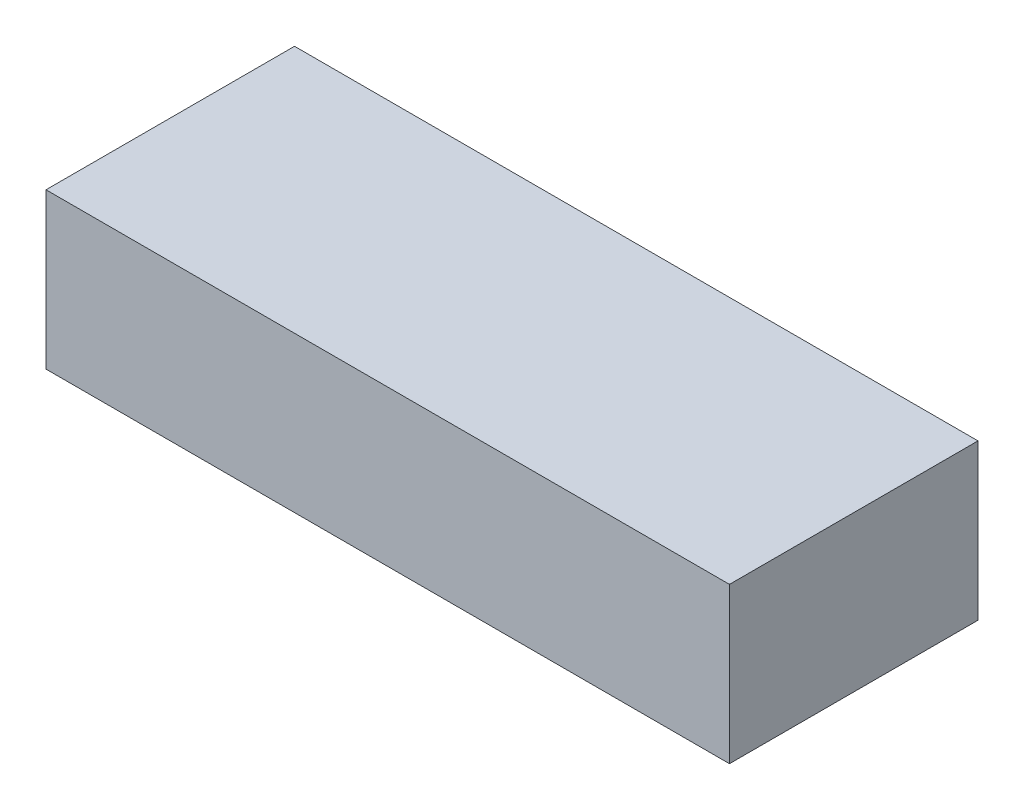
SolidWorks part; units mm, degrees
ref_plane "Front Plane" through (0, 0, 0) normal (0, 0, 1) x (1, 0, 0)
ref_plane "Top Plane" through (0, 0, 0) normal (0, 1, 0) x (1, 0, 0)
ref_plane "Right Plane" through (0, 0, 0) normal (1, 0, 0) x (0, 0, -1)
sketch "Sketch1" plane through (0, 0, 0) normal (0, 0, 1) x (1, 0, 0)
  line L1 (-34.925, -7.9375) -> (34.925, -7.9375)
  line L2 (-34.925, -7.9375) -> (-34.925, 7.9375)
  line L3 (-34.925, 7.9375) -> (34.925, 7.9375)
  line L4 (34.925, -7.9375) -> (34.925, 7.9375)
  line L5 (-34.925, -7.9375) -> (34.925, 7.9375) construction
  line L6 (-34.925, 7.9375) -> (34.925, -7.9375) construction
  point P0 (0, 0)
  dimension "D1" = 15.875
  dimension "D2" = 69.85
extrude "Boss-Extrude1" add sketch "Sketch1" along normal blind 25.4
